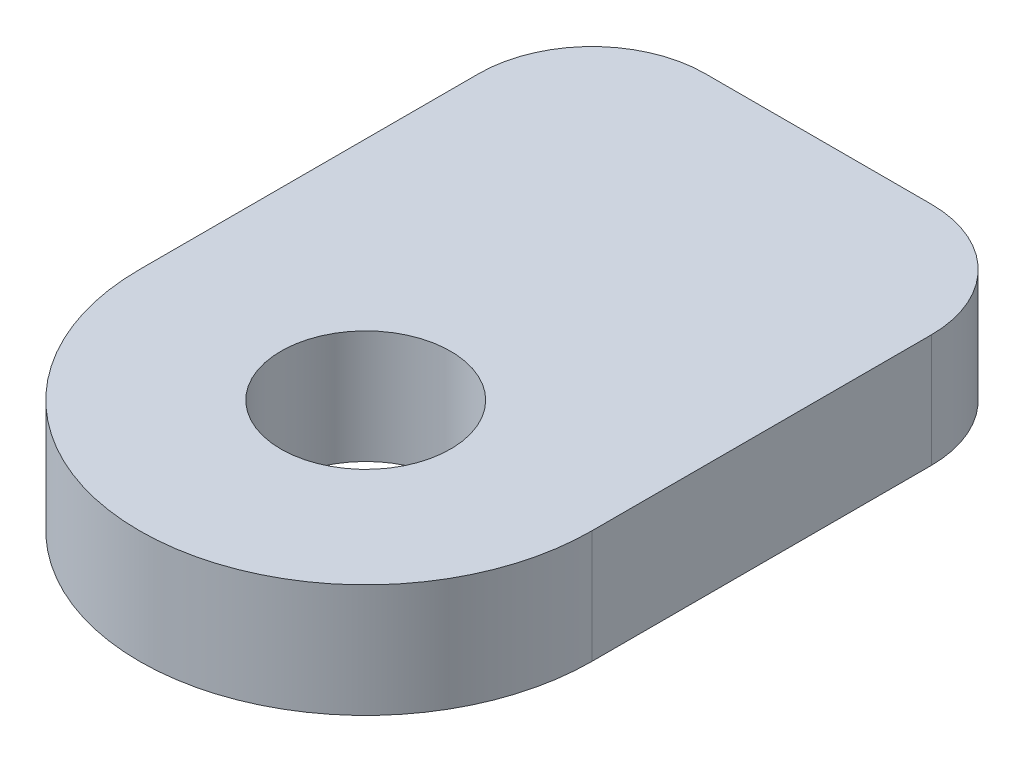
SolidWorks part; units mm, degrees
ref_plane "Front Plane" through (0, 0, 0) normal (0, 0, 1) x (1, 0, 0)
ref_plane "Top Plane" through (0, 0, 0) normal (0, 1, 0) x (1, 0, 0)
ref_plane "Right Plane" through (0, 0, 0) normal (1, 0, 0) x (0, 0, -1)
sketch "Sketch1" plane through (0, 0, 0) normal (0, 1, 0) x (1, 0, 0)
  line L0 (0, 0) -> (0, 16) construction
  line L2 (-8, 0) -> (-8, 16)
  line L3 (-8, 16) -> (8, 16)
  line L4 (8, 0) -> (8, 16)
  circle A0 centre (0, 0) radius 3
  arc A1 (-8, 0) -> (8, 0) centre (0, 0) ccw
  dimension "D2" = 16
  dimension "D3" = 6
  dimension "D1" = 16
  dimension "D4" = 16
extrude "Boss-Extrude1" add sketch "Sketch1" along normal blind 4
fillet "Fillet1" radius 4 2 edges at (8, 2, -16) (-8, 2, -16)
